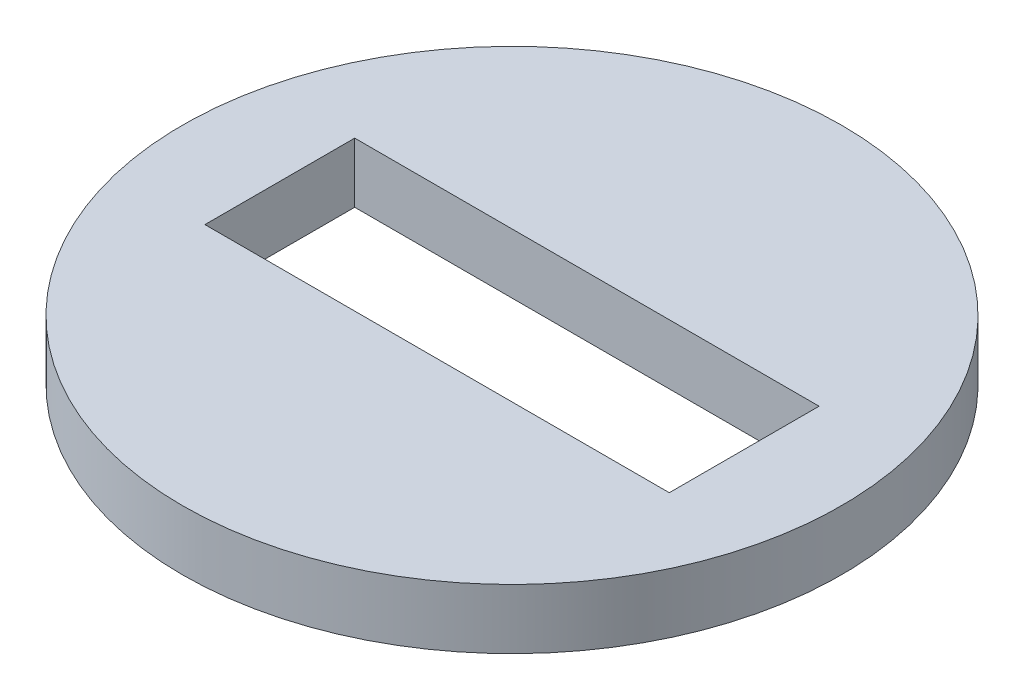
SolidWorks part; units mm, degrees
material "1.4021 (X20Cr13)"
ref_plane "Płaszczyzna przednia" through (0, 0, 0) normal (0, 0, 1) x (1, 0, 0)
ref_plane "Płaszczyzna górna" through (0, 0, 0) normal (0, 1, 0) x (1, 0, 0)
ref_plane "Płaszczyzna prawa" through (0, 0, 0) normal (1, 0, 0) x (0, 0, -1)
sketch "Szkic1" plane through (0, 0, 0) normal (0, 1, 0) x (1, 0, 0)
  line L1 (-7.75, 2.5) -> (7.75, 2.5)
  line L2 (-7.75, 2.5) -> (-7.75, -2.5)
  line L3 (-7.75, -2.5) -> (7.75, -2.5)
  line L4 (7.75, 2.5) -> (7.75, -2.5)
  circle A0 centre (0, 0) radius 11
  point P7 (0, 2.5)
  point P8 (7.75, 0)
  dimension "D3" = 22
  dimension "D1" = 15.5
  dimension "D2" = 5
extrude "Dodanie-wyciągnięcie1" add sketch "Szkic1" along normal blind 2
